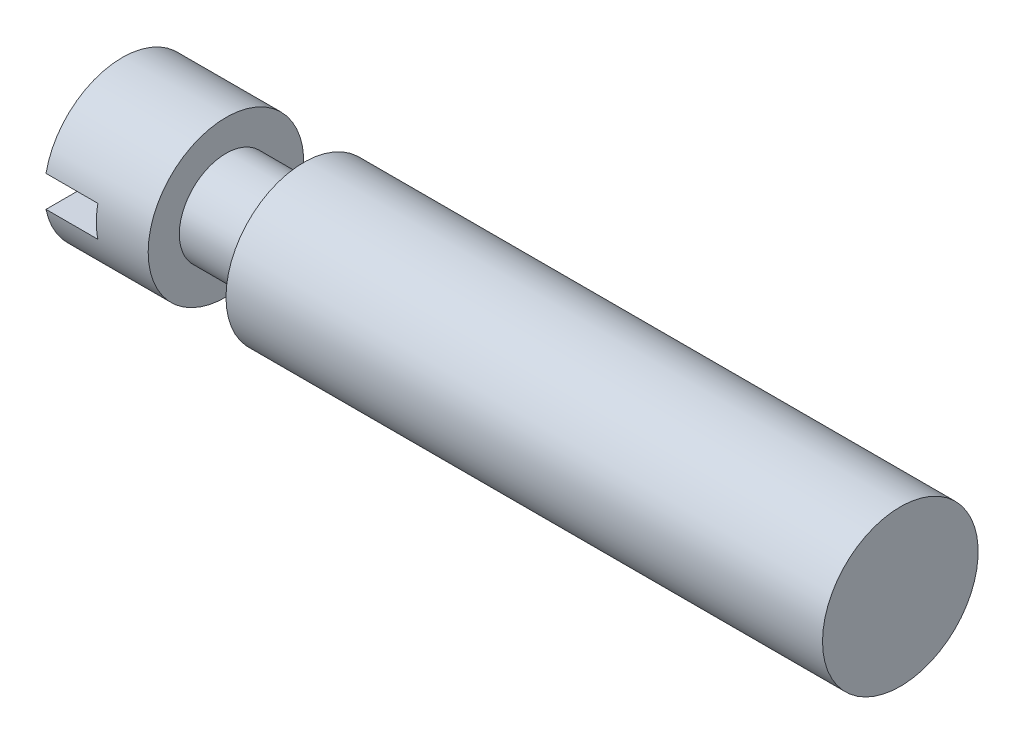
SolidWorks part; units mm, degrees
ref_plane "Front Plane" through (0, 0, 0) normal (0, 0, 1) x (1, 0, 0)
ref_plane "Top Plane" through (0, 0, 0) normal (0, 1, 0) x (1, 0, 0)
ref_plane "Right Plane" through (0, 0, 0) normal (1, 0, 0) x (0, 0, -1)
sketch "Sketch1" plane through (0, 0, 0) normal (0, 0, 1) x (1, 0, 0)
  line L0 (0, 0) -> (30, 0) construction
  line L1 (4, 3) -> (4, 1.8)
  line L2 (0, 0) -> (30, 0)
  line L3 (0, 0) -> (0, 3)
  line L4 (0, 3) -> (4, 3)
  line L5 (30, 0) -> (30, 3)
  line L6 (4, 1.8) -> (7, 1.8)
  line L7 (7, 1.8) -> (7, 3)
  line L8 (7, 3) -> (30, 3)
  dimension "D" = 6
  dimension "L" = 30
  dimension "F" = 4
  dimension "A" = 3
  dimension "D_s" = 3.6
revolve "Revolve1" add sketch "Sketch1" angle 360 about L0
cosmetic thread "Cosmetic Thread1" parameters "L_s"=16, "TD_s"=4.917
cosmetic thread "Cosmetic Thread2" [suppressed] parameters "TD_s"=2.459
sketch "Sketch2" plane through (0, 0, 0) normal (0, 0, 1) x (1, 0, 0)
  line L0 (0, 0) -> (2, 0) construction
  line L2 (0, -0.6) -> (2, -0.6)
  line L3 (0, -0.6) -> (0, 0.6)
  line L4 (0, 0.6) -> (2, 0.6)
  line L5 (2, -0.6) -> (2, 0.6)
  dimension "T" = 1.2
  dimension "H" = 2
extrude "Cut-Extrude1" cut sketch "Sketch2" against normal through all and the other way through all
